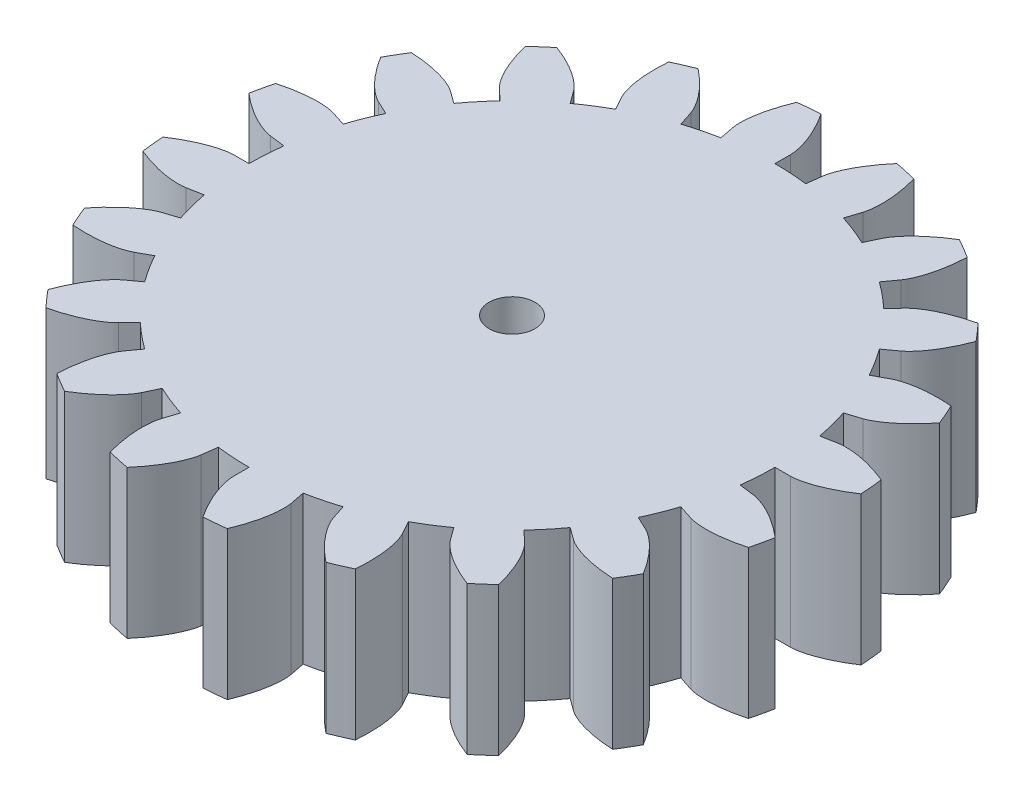
SolidWorks part; units mm, degrees
ref_plane "Front Plane" through (0, 0, 0) normal (0, 0, 1) x (1, 0, 0)
ref_plane "Top Plane" through (0, 0, 0) normal (0, 1, 0) x (1, 0, 0)
ref_plane "Right Plane" through (0, 0, 0) normal (1, 0, 0) x (0, 0, -1)
sketch "Reference attributes" plane through (0, 0, 0) normal (0, 1, 0) x (1, 0, 0)
  line L0 (0, 0) -> (20, 0) construction
  line L1 (0, -10) -> (2, -10) construction
  line L2 (0, 0) -> (19.3185, 5.1764) construction
  line L3 (0, 0) -> (18.7939, 6.8404) construction
  dimension "Teeth" = 20
  dimension "Module" = 2
  dimension "D2" = 10
  dimension "Helix Angle" = 15
  dimension "Pressure angle" = 20
sketch "Gear billet" plane through (0, 0, 0) normal (0, 1, 0) x (1, 0, 0)
  circle A0 centre (0, 0) radius 22.25
  dimension "OuterDi" = 44.5
extrude "Gear billet Extrude" add sketch "Gear billet" along normal blind 10
ref_plane "Opposite gear face" through (0, 10, 0) normal (0, 1, 0) x (1, 0, 0)
ref_point "Twist centre point top"
ref_point "Twist centre point bottom"
ref_axis "Axis" through (0, 10, 0) along (0, -1, 0)
sketch "Involute Profile" plane through (0, 10, 0) normal (0, 1, 0) x (1, 0, 0)
  line L0 (0, 0) -> (0, 18.7939) construction
  line L1 (0, 0) -> (2.3438, 18.6471) construction
  circle A0 centre (0, 0) radius 20.25
  circle A4 centre (0, 0) radius 18.7939 construction
  spline S0 degree 4 poles (0, 18.7939) (0, 18.8518) (-0.0077, 19.0141) (-0.0532, 19.3212) (-0.1702, 19.8117) (-0.3844, 20.4293) (-0.7301, 21.1949) (-1.2195, 22.0492) (-1.8405, 22.9346) (-2.5915, 23.8263) (-3.41, 24.6558) (-4.2862, 25.4242) (-5.2572, 26.1674) (-6.5181, 27.0058) (-8.0992, 27.88) (-10.0226, 28.7202) (-12.2415, 29.4385) (-14.5165, 29.9502) (-16.8267, 30.2641) (-19.1546, 30.389) (-21.4848, 30.3335) (-23.8046, 30.1059) (-25.8148, 29.7638) (-27.3763, 29.4056) (-28.4998, 29.1018) (-29.1992, 28.8961) (-29.7524, 28.7239) (-30.3106, 28.5395) (-30.851, 28.3524) (-31.3658, 28.1638) (-31.7844, 28.0051) (-32.2576, 27.8177) (-32.5635, 27.6931) (-33.0543, 27.4877) (-33.4354, 27.3203) (-33.8934, 27.1155) (-34.3016, 26.9247) (-34.7364, 26.7169) (-35.1499, 26.5116) (-35.4687, 26.3496) (-35.6753, 26.242) (-35.7794, 26.1873) knots 0 0 0 0 0 0.005604 0.015718 0.02996 0.048734 0.068727 0.096889 0.125051 0.153212 0.181374 0.209535 0.237696 0.271429 0.327752 0.384075 0.440398 0.496721 0.553044 0.609367 0.66569 0.722013 0.778336 0.806497 0.820578 0.834659 0.84874 0.86282 0.876901 0.890982 0.900036 0.909091 0.920455 0.931818 0.943182 0.954545 0.965909 0.977273 0.988636 1 1 1 1 1 construction
  spline S1 degree 4 poles (0, 18.7939) (0, 18.8518) (-0.0077, 19.0141) (-0.0532, 19.3212) (-0.1702, 19.8117) (-0.3844, 20.4293) (-0.7301, 21.1949) (-1.2195, 22.0492) (-1.8405, 22.9346) (-2.5915, 23.8263) (-3.41, 24.6558) (-4.2862, 25.4242) (-5.2572, 26.1674) (-6.5181, 27.0058) (-8.0992, 27.88) (-10.0226, 28.7202) (-12.2415, 29.4385) (-14.5165, 29.9502) (-16.8267, 30.2641) (-19.1546, 30.389) (-21.4848, 30.3335) (-23.8046, 30.1059) (-25.8148, 29.7638) (-27.3763, 29.4056) (-28.4998, 29.1018) (-29.1992, 28.8961) (-29.7524, 28.7239) (-30.3106, 28.5395) (-30.851, 28.3524) (-31.3658, 28.1638) (-31.7844, 28.0051) (-32.1341, 27.8666) (-32.2933, 27.8026) (-32.3722, 27.7706) knots 0 0 0 0 0 0.005604 0.015718 0.02996 0.048734 0.068727 0.096889 0.125051 0.153212 0.181374 0.209535 0.237696 0.271429 0.327752 0.384075 0.440398 0.496721 0.553044 0.609367 0.66569 0.722013 0.778336 0.806497 0.820578 0.834659 0.84874 0.86282 0.876901 0.890982 0.900036 0.909091 0.909091 0.909091 0.909091 0.909091
  spline S2 degree 4 poles (2.3438, 18.6471) (2.351, 18.7047) (2.3789, 18.8647) (2.4623, 19.1638) (2.6396, 19.6358) (2.9292, 20.2219) (3.3676, 20.9384) (3.9597, 21.725) (4.6863, 22.526) (5.5426, 23.3171) (6.4582, 24.038) (7.4234, 24.6912) (8.4795, 25.3075) (9.8351, 25.9821) (11.5128, 26.6523) (13.526, 27.2461) (15.8172, 27.6821) (18.1382, 27.906) (20.4696, 27.9294) (22.7949, 27.763) (25.1, 27.4173) (27.3733, 26.9022) (29.3251, 26.3121) (30.8298, 25.762) (31.9066, 25.3204) (32.5749, 25.0291) (33.1023, 24.7892) (33.6332, 24.5367) (34.146, 24.2837) (34.6333, 24.0323) (35.0288, 23.8226) (35.4749, 23.5777) (35.7629, 23.4159) (36.2243, 23.1509) (36.5815, 22.9373) (37.0104, 22.677) (37.3916, 22.4367) (37.7971, 22.1763) (38.1818, 21.9211) (38.4778, 21.7206) (38.6694, 21.588) (38.7659, 21.5208) knots 0 0 0 0 0 0.005604 0.015718 0.02996 0.048734 0.068727 0.096889 0.125051 0.153212 0.181374 0.209535 0.237696 0.271429 0.327752 0.384075 0.440398 0.496721 0.553044 0.609367 0.66569 0.722013 0.778336 0.806497 0.820578 0.834659 0.84874 0.86282 0.876901 0.890982 0.900036 0.909091 0.920455 0.931818 0.943182 0.954545 0.965909 0.977273 0.988636 1 1 1 1 1 construction
  spline S3 degree 4 poles (2.3438, 18.6471) (2.351, 18.7047) (2.3789, 18.8647) (2.4623, 19.1638) (2.6396, 19.6358) (2.9292, 20.2219) (3.3676, 20.9384) (3.9597, 21.725) (4.6863, 22.526) (5.5426, 23.3171) (6.4582, 24.038) (7.4234, 24.6912) (8.4795, 25.3075) (9.8351, 25.9821) (11.5128, 26.6523) (13.526, 27.2461) (15.8172, 27.6821) (18.1382, 27.906) (20.4696, 27.9294) (22.7949, 27.763) (25.1, 27.4173) (27.3733, 26.9022) (29.3251, 26.3121) (30.8298, 25.762) (31.9066, 25.3204) (32.5749, 25.0291) (33.1023, 24.7892) (33.6332, 24.5367) (34.146, 24.2837) (34.6333, 24.0323) (35.0288, 23.8226) (35.3585, 23.6416) (35.5085, 23.5583) (35.5827, 23.5167) knots 0 0 0 0 0 0.005604 0.015718 0.02996 0.048734 0.068727 0.096889 0.125051 0.153212 0.181374 0.209535 0.237696 0.271429 0.327752 0.384075 0.440398 0.496721 0.553044 0.609367 0.66569 0.722013 0.778336 0.806497 0.820578 0.834659 0.84874 0.86282 0.876901 0.890982 0.900036 0.909091 0.909091 0.909091 0.909091 0.909091
  point P6 (-0.3292, 20.2473)
  point P11 (2.8517, 20.0482)
  dimension "BaseDi" = 37.5877
  dimension "Adjusted Reference Diameter" = 40.5
  dimension "Reference Circumferential pitch" = 3.1809
sketch "Tooth profile" plane through (0, 10, 0) normal (0, 1, 0) x (1, 0, 0)
  line L0 (0, 0) -> (0, 18.7939) construction
  line L1 (0, 0) -> (2.3438, 18.6471) construction
  line L2 (0, 0) -> (0, 18.7939)
  line L3 (0, 0) -> (2.3438, 18.6471)
  line L4 (-0.2, -3.1949) -> (-0.2, 18.7939) construction
  line L5 (-0.2, -3.1949) -> (2.5422, 18.6222) construction
  circle A0 centre (0, 0) radius 22.25 construction
  circle A1 centre (0, 0) radius 22.25
  circle A2 centre (0, 0) radius 17.75
  spline S0 degree 1 poles (-0.2, 18.7939) (-32.2969, 27.5853) knots 0 0 1 1 construction
  spline S1 degree 4 poles (-1998.4723, 93.353) (-60.8254, 11.2844) (-1.3865, 12.9431) (0.6037, 16.5702) (-0.1702, 19.8117) (-0.3844, 20.4293) (-0.7301, 21.1949) (-1.2195, 22.0492) (-1.8405, 22.9346) (-2.5915, 23.8263) (-3.41, 24.6558) (-4.2862, 25.4242) (-5.2572, 26.1674) (-6.5181, 27.0058) (-8.0992, 27.88) (-10.0226, 28.7202) (-12.2415, 29.4385) (-14.5165, 29.9502) (-16.8267, 30.2641) (-19.1546, 30.389) (-21.4848, 30.3335) (-23.8046, 30.1059) (-25.8148, 29.7638) (-27.3763, 29.4056) (-28.4998, 29.1018) (-29.1992, 28.8961) (-29.7524, 28.7239) (-30.3106, 28.5395) (-30.851, 28.3524) (-31.3658, 28.1638) (-33.2605, 27.4454) (-37.1849, 25.7418) (13.5687, 46.1249) (-1884.9634, -725.2927) knots -0.273368 -0.273368 -0.273368 -0.273368 -0.273368 0.005604 0.015718 0.02996 0.048734 0.068727 0.096889 0.125051 0.153212 0.181374 0.209535 0.237696 0.271429 0.327752 0.384075 0.440398 0.496721 0.553044 0.609367 0.66569 0.722013 0.778336 0.806497 0.820578 0.834659 0.84874 0.86282 0.876901 0.890982 0.900036 1.072272 1.072272 1.072272 1.072272 1.072272 only from (0, 18.7939) to (-32.3722, 27.7706) construction
  spline S2 degree 4 poles (1994.5128, -156.6052) (61.7579, 3.6108) (2.9898, 12.6691) (1.4675, 16.5161) (2.6396, 19.6358) (2.9292, 20.2219) (3.3676, 20.9384) (3.9597, 21.725) (4.6863, 22.526) (5.5426, 23.3171) (6.4582, 24.038) (7.4234, 24.6912) (8.4795, 25.3075) (9.8351, 25.9821) (11.5128, 26.6523) (13.526, 27.2461) (15.8172, 27.6821) (18.1382, 27.906) (20.4696, 27.9294) (22.7949, 27.763) (25.1, 27.4173) (27.3733, 26.9022) (29.3251, 26.3121) (30.8298, 25.762) (31.9066, 25.3204) (32.5749, 25.0291) (33.1023, 24.7892) (33.6332, 24.5367) (34.146, 24.2837) (34.6333, 24.0323) (36.4235, 23.0832) (40.1049, 20.9035) (-7.7106, 47.457) (1779.7967, -954.7042) knots -0.273368 -0.273368 -0.273368 -0.273368 -0.273368 0.005604 0.015718 0.02996 0.048734 0.068727 0.096889 0.125051 0.153212 0.181374 0.209535 0.237696 0.271429 0.327752 0.384075 0.440398 0.496721 0.553044 0.609367 0.66569 0.722013 0.778336 0.806497 0.820578 0.834659 0.84874 0.86282 0.876901 0.890982 0.900036 1.072272 1.072272 1.072272 1.072272 1.072272 only from (2.3438, 18.6471) to (35.5827, 23.5167) construction
  spline S3 degree 1 poles (2.5422, 18.6222) (35.4849, 23.3422) knots 0 0 1 1 construction
  spline S4 degree 4 poles (0, 18.7939) (0, 18.8518) (-0.0077, 19.0141) (-0.0532, 19.3212) (-0.1702, 19.8117) (-0.3844, 20.4293) (-0.7301, 21.1949) (-1.2195, 22.0492) (-1.8405, 22.9346) (-2.5915, 23.8263) (-3.41, 24.6558) (-4.2862, 25.4242) (-5.2572, 26.1674) (-6.5181, 27.0058) (-8.0992, 27.88) (-10.0226, 28.7202) (-12.2415, 29.4385) (-14.5165, 29.9502) (-16.8267, 30.2641) (-19.1546, 30.389) (-21.4848, 30.3335) (-23.8046, 30.1059) (-25.8148, 29.7638) (-27.3763, 29.4056) (-28.4998, 29.1018) (-29.1992, 28.8961) (-29.7524, 28.7239) (-30.3106, 28.5395) (-30.851, 28.3524) (-31.3658, 28.1638) (-31.7844, 28.0051) (-32.1341, 27.8666) (-32.2933, 27.8026) (-32.3722, 27.7706) knots 0 0 0 0 0 0.005604 0.015718 0.02996 0.048734 0.068727 0.096889 0.125051 0.153212 0.181374 0.209535 0.237696 0.271429 0.327752 0.384075 0.440398 0.496721 0.553044 0.609367 0.66569 0.722013 0.778336 0.806497 0.820578 0.834659 0.84874 0.86282 0.876901 0.890982 0.900036 0.909091 0.909091 0.909091 0.909091 0.909091
  spline S5 degree 4 poles (2.3438, 18.6471) (2.351, 18.7047) (2.3789, 18.8647) (2.4623, 19.1638) (2.6396, 19.6358) (2.9292, 20.2219) (3.3676, 20.9384) (3.9597, 21.725) (4.6863, 22.526) (5.5426, 23.3171) (6.4582, 24.038) (7.4234, 24.6912) (8.4795, 25.3075) (9.8351, 25.9821) (11.5128, 26.6523) (13.526, 27.2461) (15.8172, 27.6821) (18.1382, 27.906) (20.4696, 27.9294) (22.7949, 27.763) (25.1, 27.4173) (27.3733, 26.9022) (29.3251, 26.3121) (30.8298, 25.762) (31.9066, 25.3204) (32.5749, 25.0291) (33.1023, 24.7892) (33.6332, 24.5367) (34.146, 24.2837) (34.6333, 24.0323) (35.0288, 23.8226) (35.3585, 23.6416) (35.5085, 23.5583) (35.5827, 23.5167) knots 0 0 0 0 0 0.005604 0.015718 0.02996 0.048734 0.068727 0.096889 0.125051 0.153212 0.181374 0.209535 0.237696 0.271429 0.327752 0.384075 0.440398 0.496721 0.553044 0.609367 0.66569 0.722013 0.778336 0.806497 0.820578 0.834659 0.84874 0.86282 0.876901 0.890982 0.900036 0.909091 0.909091 0.909091 0.909091 0.909091
  spline S6 degree 3 poles (-32.2969, 27.5853) (-29.42, 28.7538) (-24.8533, 29.9764) (-18.6196, 30.2613) (-13.9671, 29.7385) (-9.4789, 28.4087) (-6.0363, 26.5692) (-3.6149, 24.6265) (-2.0307, 22.9253) (-0.9698, 21.3081) (-0.3887, 19.8838) (-0.2, 19.1635) (-0.2, 18.7939) knots 0 0 0 0 0.227273 0.340909 0.454545 0.568182 0.681818 0.738636 0.795455 0.852273 0.880682 0.909091 0.909091 0.909091 0.909091 construction
  spline S7 degree 3 poles (2.5422, 18.6222) (2.5883, 18.9889) (2.8654, 19.6801) (3.6196, 21.0208) (4.8738, 22.4931) (6.6579, 23.9834) (9.3027, 25.609) (12.9478, 27.0048) (17.5667, 27.7646) (22.2481, 27.703) (28.3977, 26.643) (32.7762, 24.8603) (35.4849, 23.3422) knots 0 0 0 0 0.028409 0.056818 0.113636 0.170455 0.227273 0.340909 0.454545 0.568182 0.681818 0.909091 0.909091 0.909091 0.909091 construction
  dimension "RootDi" = 35.5
  dimension "Offset" = 0.2
extrude "Cut tooth profile" cut sketch "Tooth profile" against normal up to next
sketch "Tooth profile OFFSET" plane through (0, 10, 0) normal (0, 1, 0) x (1, 0, 0)
  line L4 (-0.1, -1.5975) -> (-0.1, 18.7939)
  line L5 (2.443, 18.6347) -> (-0.1, -1.5975)
  line L6 (-0.1, -1.5975) -> (-0.1, 18.7939)
  line L7 (2.443, 18.6347) -> (-0.1, -1.5975)
  circle A3 centre (0, 0) radius 22.25 construction
  circle A4 centre (0, 0) radius 22.25
  circle A6 centre (0, 0) radius 17.65
  circle A7 centre (0, 0) radius 17.65
  spline S4 degree 3 poles (2649.0198, -1449.0371) (-2.6913, 41.8387) (42.7152, 19.4777) (35.2011, 23.6137) (35.1083, 23.6644) (34.8414, 23.8087) (34.6772, 23.8955) (34.3324, 24.0746) (34.1548, 24.1653) (33.8054, 24.3399) (33.632, 24.4247) (32.7517, 24.8471) (32.036, 25.1625) (29.8624, 26.0348) (28.3739, 26.5198) (25.3429, 27.2708) (23.8, 27.537) (20.6915, 27.8237) (19.1255, 27.8442) (16.0138, 27.6106) (14.4676, 27.3564) (11.4573, 26.5413) (9.9922, 25.9805) (7.9295, 24.8824) (7.2648, 24.4736) (6.0008, 23.5652) (5.4012, 23.0657) (4.2985, 21.9703) (3.7937, 21.3744) (3.1555, 20.4034) (2.9622, 20.0667) (2.7184, 19.5423) (2.6451, 19.3641) (-0.582, 10.0165) (18.3168, -6.5846) (2950.9982, 569.7854) knots -0.654834 -0.654834 -0.654834 -0.654834 0.007812 0.007812 0.015625 0.015625 0.03125 0.03125 0.046875 0.046875 0.0625 0.0625 0.125 0.125 0.25 0.25 0.375 0.375 0.5 0.5 0.625 0.625 0.75 0.75 0.8125 0.8125 0.875 0.875 0.9375 0.9375 0.96875 0.96875 0.984375 0.984375 1.774134 1.774134 1.774134 1.774134 only from (35.5338, 23.4294) to (2.443, 18.6347)
  spline S5 degree 3 poles (-2857.1014, 933.4217) (-18.996, -4.2495) (1.8266, 9.8655) (-0.2096, 19.5429) (-0.2601, 19.7287) (-0.4365, 20.2795) (-0.5863, 20.6376) (-1.0985, 21.6806) (-1.525, 22.3348) (-2.4825, 23.5592) (-3.0151, 24.1296) (-4.1559, 25.1885) (-4.7645, 25.6771) (-6.6742, 27.0238) (-8.0579, 27.7629) (-10.943, 28.947) (-12.4454, 29.3921) (-15.5038, 30.012) (-17.06, 30.1869) (-20.1801, 30.2901) (-21.7441, 30.2184) (-24.8451, 29.8513) (-26.3825, 29.5557) (-28.6479, 28.9613) (-29.3973, 28.7376) (-30.3234, 28.4283) (-30.5061, 28.3658) (-30.8746, 28.2361) (-31.062, 28.1683) (-31.4265, 28.0335) (-31.6003, 27.9679) (-31.8831, 27.858) (-31.9815, 27.8193) (-39.9526, 24.6526) (7.888, 41.1764) (-2809.0529, -1107.3673) knots -0.774153 -0.774153 -0.774153 -0.774153 0.015625 0.015625 0.03125 0.03125 0.0625 0.0625 0.125 0.125 0.1875 0.1875 0.25 0.25 0.375 0.375 0.5 0.5 0.625 0.625 0.75 0.75 0.875 0.875 0.9375 0.9375 0.953125 0.953125 0.96875 0.96875 0.984375 0.984375 0.992188 0.992188 1.654834 1.654834 1.654834 1.654834 only from (-0.1, 18.7939) to (-32.3345, 27.6779)
  spline S6 degree 3 poles (35.5338, 23.4294) (35.4564, 23.4728) (35.3762, 23.5173) (35.2011, 23.6137) (35.1083, 23.6644) (34.8414, 23.8087) (34.6772, 23.8955) (34.3324, 24.0746) (34.1548, 24.1653) (33.8054, 24.3399) (33.632, 24.4247) (32.7517, 24.8471) (32.036, 25.1625) (29.8624, 26.0348) (28.3739, 26.5198) (25.3429, 27.2708) (23.8, 27.537) (20.6915, 27.8237) (19.1255, 27.8442) (16.0138, 27.6106) (14.4676, 27.3564) (11.4573, 26.5413) (9.9922, 25.9805) (7.9295, 24.8824) (7.2648, 24.4736) (6.0008, 23.5652) (5.4012, 23.0657) (4.2985, 21.9703) (3.7937, 21.3744) (3.1555, 20.4034) (2.9622, 20.0667) (2.7184, 19.5423) (2.6451, 19.3641) (2.5199, 19.0014) (2.4659, 18.8172) (2.443, 18.6347) knots 0 0 0 0 0.007812 0.007812 0.015625 0.015625 0.03125 0.03125 0.046875 0.046875 0.0625 0.0625 0.125 0.125 0.25 0.25 0.375 0.375 0.5 0.5 0.625 0.625 0.75 0.75 0.8125 0.8125 0.875 0.875 0.9375 0.9375 0.96875 0.96875 0.984375 0.984375 1 1 1 1
  spline S7 degree 3 poles (-0.1, 18.7939) (-0.1, 18.9778) (-0.1306, 19.1674) (-0.2096, 19.5429) (-0.2601, 19.7287) (-0.4365, 20.2795) (-0.5863, 20.6376) (-1.0985, 21.6806) (-1.525, 22.3348) (-2.4825, 23.5592) (-3.0151, 24.1296) (-4.1559, 25.1885) (-4.7645, 25.6771) (-6.6742, 27.0238) (-8.0579, 27.7629) (-10.943, 28.947) (-12.4454, 29.3921) (-15.5038, 30.012) (-17.06, 30.1869) (-20.1801, 30.2901) (-21.7441, 30.2184) (-24.8451, 29.8513) (-26.3825, 29.5557) (-28.6479, 28.9613) (-29.3973, 28.7376) (-30.3234, 28.4283) (-30.5061, 28.3658) (-30.8746, 28.2361) (-31.062, 28.1683) (-31.4265, 28.0335) (-31.6003, 27.9679) (-31.8831, 27.858) (-31.9815, 27.8193) (-32.1672, 27.7455) (-32.2524, 27.7113) (-32.3345, 27.6779) knots 0 0 0 0 0.015625 0.015625 0.03125 0.03125 0.0625 0.0625 0.125 0.125 0.1875 0.1875 0.25 0.25 0.375 0.375 0.5 0.5 0.625 0.625 0.75 0.75 0.875 0.875 0.9375 0.9375 0.953125 0.953125 0.96875 0.96875 0.984375 0.984375 0.992188 0.992188 1 1 1 1
  line M3 (0, 17.75) -> (0, 18.7939)
  spline M4 degree 4 poles (0, 18.7939) (0, 18.8518) (-0.0077, 19.0141) (-0.0532, 19.3212) (-0.1702, 19.8117) (-0.3844, 20.4293) (-0.7301, 21.1949) (-1.2195, 22.0492) (-1.8405, 22.9346) (-2.5915, 23.8263) (-3.41, 24.6558) (-4.2862, 25.4242) (-5.2572, 26.1674) (-6.5181, 27.0058) (-8.0992, 27.88) (-10.0226, 28.7202) (-12.2415, 29.4385) (-14.5165, 29.9502) (-16.8267, 30.2641) (-19.1546, 30.389) (-21.4848, 30.3335) (-23.8046, 30.1059) (-25.8148, 29.7638) (-27.3763, 29.4056) (-28.4998, 29.1018) (-29.1992, 28.8961) (-29.7524, 28.7239) (-30.3106, 28.5395) (-30.851, 28.3524) (-31.3658, 28.1638) (-31.7844, 28.0051) (-32.1341, 27.8666) (-32.2933, 27.8026) (-32.3722, 27.7706) knots 0 0 0 0 0 0.005604 0.015718 0.02996 0.048734 0.068727 0.096889 0.125051 0.153212 0.181374 0.209535 0.237696 0.271429 0.327752 0.384075 0.440398 0.496721 0.553044 0.609367 0.66569 0.722013 0.778336 0.806497 0.820578 0.834659 0.84874 0.86282 0.876901 0.890982 0.900036 0.909091 0.909091 0.909091 0.909091 0.909091 only from (0, 18.7939) to (-1.348, 22.2091)
  arc M5 (-1.348, 22.2091) -> (4.1072, 21.8676) centre (0, 0) ccw
  spline M6 degree 4 poles (35.5827, 23.5167) (35.5085, 23.5583) (35.3585, 23.6416) (35.0288, 23.8226) (34.6333, 24.0323) (34.146, 24.2837) (33.6332, 24.5367) (33.1023, 24.7892) (32.5749, 25.0291) (31.9066, 25.3204) (30.8298, 25.762) (29.3251, 26.3121) (27.3733, 26.9022) (25.1, 27.4173) (22.7949, 27.763) (20.4696, 27.9294) (18.1382, 27.906) (15.8172, 27.6821) (13.526, 27.2461) (11.5128, 26.6523) (9.8351, 25.9821) (8.4795, 25.3075) (7.4234, 24.6912) (6.4582, 24.038) (5.5426, 23.3171) (4.6863, 22.526) (3.9597, 21.725) (3.3676, 20.9384) (2.9292, 20.2219) (2.6396, 19.6358) (2.4623, 19.1638) (2.3789, 18.8647) (2.351, 18.7047) (2.3438, 18.6471) knots 0 0 0 0 0 0.009054 0.018109 0.03219 0.04627 0.060351 0.074432 0.088513 0.102594 0.130755 0.187078 0.243401 0.299724 0.356047 0.41237 0.468693 0.525016 0.581339 0.637662 0.671395 0.699556 0.727717 0.755879 0.78404 0.812202 0.840364 0.860357 0.879131 0.893373 0.903487 0.909091 0.909091 0.909091 0.909091 0.909091 only from (4.1072, 21.8676) to (2.3438, 18.6471)
  line M7 (2.3438, 18.6471) -> (2.2136, 17.6114)
  arc M8 (2.2136, 17.6114) -> (0, 17.75) centre (0, 0) ccw
  dimension "Offset" = 0.1
  dimension "D2" = 0.1
extrude "Cut Tooth profile OFFSET" [suppressed] cut sketch "Tooth profile OFFSET" against normal up to surface (10 mm away) contours S7 L6 A7 L7 S6 A4 M6 M7 M8 M3 M4 M5
sketch "Tangent meshing reference" plane through (0, 10, 0) normal (0, 1, 0) x (1, 0, 0)
  circle A0 centre (0, 0) radius 20.25 construction
  circle A1 centre (0, 0) radius 20.25
sketch "Gear ratio reference" plane through (0, 10, 0) normal (0, 1, 0) x (1, 0, 0)
  circle A0 centre (0, 0) radius 20
  dimension "Reference diameter" = 40
pattern_circular "Duplicate teeth" count 20 over 360 about axis through (0, 10, 0) along (0, -1, 0) of "Cut tooth profile"
other "Twist Left" [suppressed] parameters "D0"=7.581
other "Twist Right" [suppressed] parameters "D0"=7.581
mirror "Herringbone Mirror" [suppressed] about plane through (0, 10, 0) normal (0, 1, 0)
sketch "Sketch1" plane through (0, 0, 0) normal (0, -1, 0) x (1, 0, 0)
  circle A0 centre (0, 0) radius 1.55
  dimension "D1" = 3.1
extrude "Cut-Extrude1" cut sketch "Sketch1" against normal up to surface (10 mm away) up to face at (0, 10, 0)
equation "\"D1@Duplicate teeth\"=\"Teeth@Reference attributes\""
equation "\"twist\"= \"suppressed\""
equation "\"D2@Tooth profile OFFSET\"=\"Offset@Tooth profile OFFSET\""
